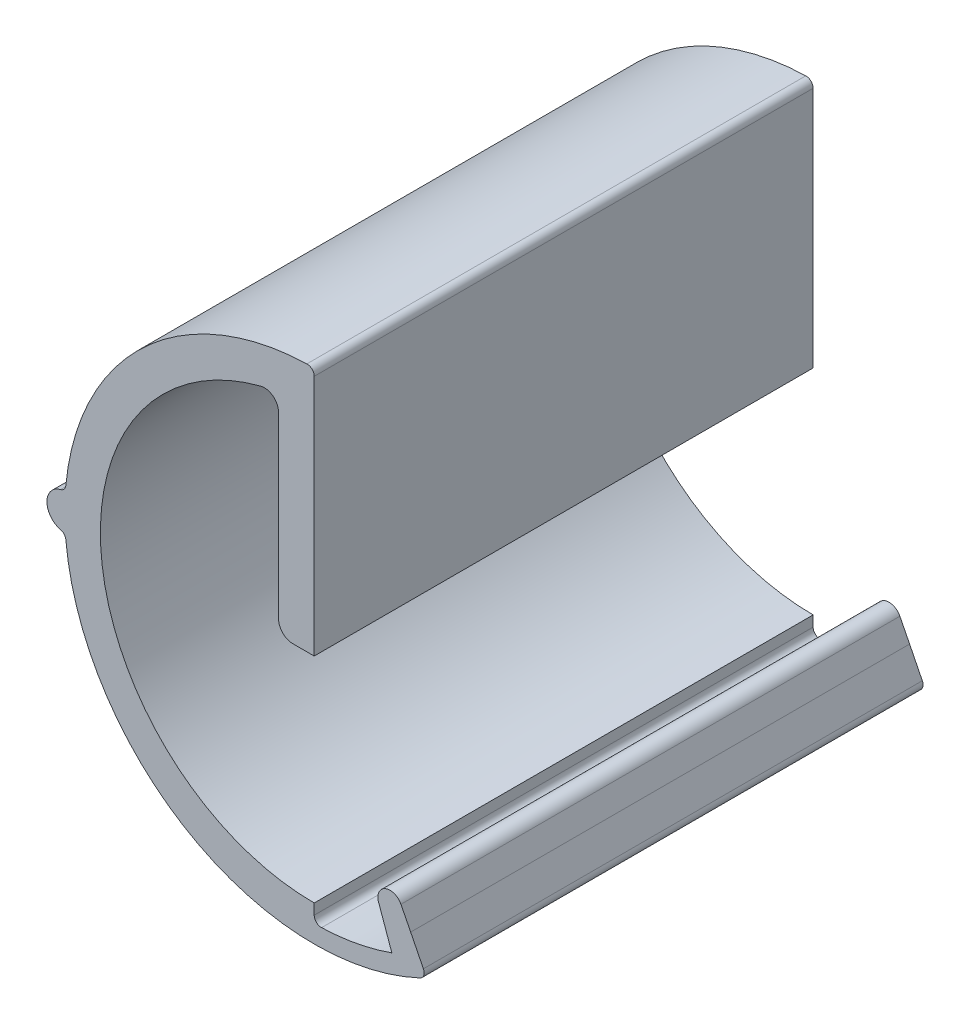
SolidWorks part; units mm, degrees
material "Pine"
ref_plane "Front Plane" through (0, 0, 0) normal (0, 0, 1) x (1, 0, 0)
ref_plane "Top Plane" through (0, 0, 0) normal (0, 1, 0) x (1, 0, 0)
ref_plane "Right Plane" through (0, 0, 0) normal (1, 0, 0) x (0, 0, -1)
sketch "Sketch1" plane through (0, 0, 0) normal (0, 0, 1) x (1, 0, 0)
  line L0 (0, 35) -> (0, 0)
  line L1 (13.5338, -26.7738) -> (15.7714, -31.2452)
  line L2 (0, -30) -> (0, -32.5)
  line L3 (10.8934, -30.62) -> (9.1146, -25.62)
  line L4 (13.5338, -26.7738) -> (12.1699, -24.0756)
  line L5 (0, 0) -> (-5, 0)
  line L6 (-5, 0) -> (-5, 29.5804)
  line L8 (0, 0) -> (-5, 0) construction
  line L10 (-30, 0) -> (-35, 0) construction
  arc A0 (0, 35) -> (-34.9107, 2.4984) centre (0, 0) ccw
  arc A1 (-5, 29.5804) -> (0, -30) centre (0, 0) ccw
  arc A2 (0, -32.5) -> (10.8934, -30.62) centre (0, 0) ccw
  arc A3 (12.1699, -24.0756) -> (9.1146, -25.62) centre (10.6423, -24.8478) ccw
  arc A4 (-34.9107, 2.4984) -> (-34.9107, -2.4984) centre (-35, 0) ccw
  arc A5 (-34.9107, -2.4984) -> (15.7714, -31.2452) centre (0, 0) ccw
  dimension "D1" = 70
  dimension "D2" = 60
  dimension "D3" = 65
  dimension "D5" = 5
  dimension "D6" = 1.7118
  dimension "D9" = 5
  dimension "D4" = 5
  dimension "D7" = 9.1146
  dimension "D8" = 10.6423
  dimension "D12" = 15.7714
extrude "Boss-Extrude1" add sketch "Sketch1" against normal blind 70
fillet "Fillet1" radius 2 1 edges at (-5, 0, -35)
fillet "Fillet2" radius 2 1 edges at (-5, 29.5804, -35)
fillet "Fillet3" radius 1 1 edges at (0, -32.5, -35)
fillet "Fillet4" radius 1 1 edges at (15.7714, -31.2452, -35)
fillet "Fillet5" radius 1 2 edges at (-34.9107, -2.4984, -35) (-34.9107, 2.4984, -35)
fillet "Fillet6" radius 1 1 edges at (0, 35, -35)
